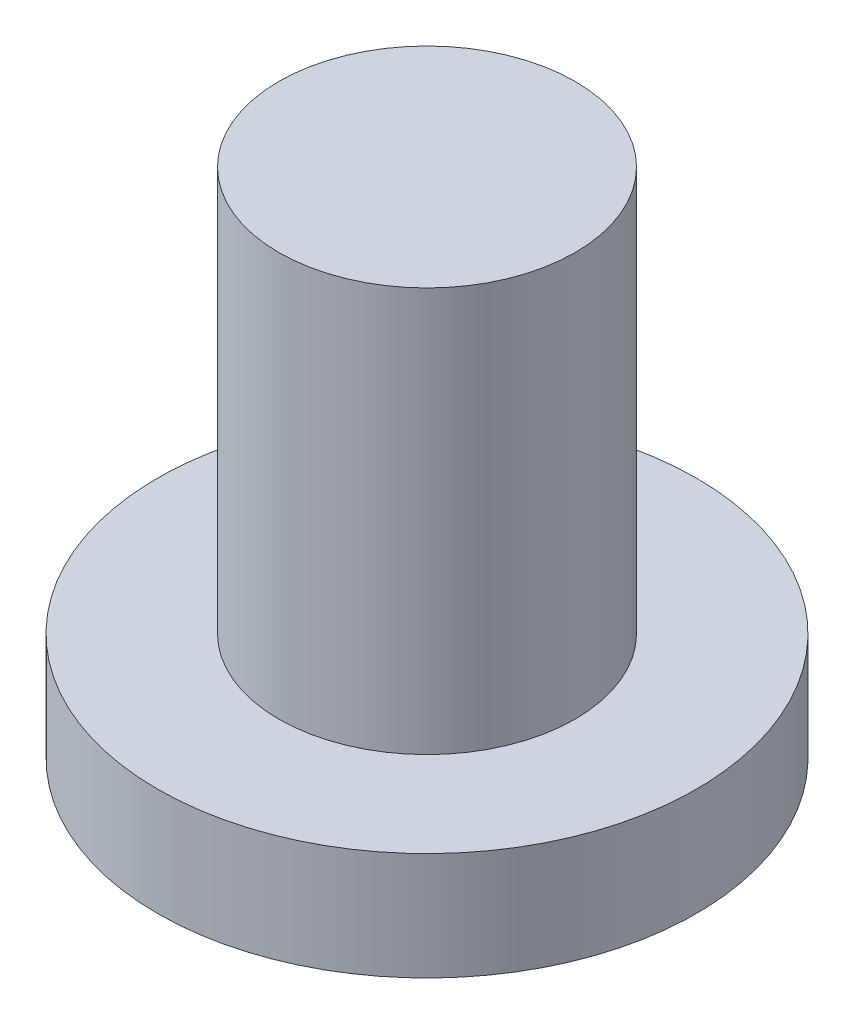
SolidWorks part; units mm, degrees
ref_plane "Plano frontal" through (0, 0, 0) normal (0, 0, 1) x (1, 0, 0)
ref_plane "Plano superior" through (0, 0, 0) normal (0, 1, 0) x (1, 0, 0)
ref_plane "Plano direito" through (0, 0, 0) normal (1, 0, 0) x (0, 0, -1)
sketch "Esboço1" plane through (0, 0, 0) normal (0, 1, 0) x (1, 0, 0)
  circle A0 centre (0, 0) radius 2
  dimension "D1" = 4
extrude "Ressalto-extrusão1" add sketch "Esboço1" along normal blind 0.8
sketch "Esboço2" plane through (0, 0.8, 0) normal (0, 1, 0) x (1, 0, 0)
  circle A0 centre (0, 0) radius 1.1
  dimension "D1" = 2.2
extrude "Ressalto-extrusão2" add sketch "Esboço2" along normal blind 3
